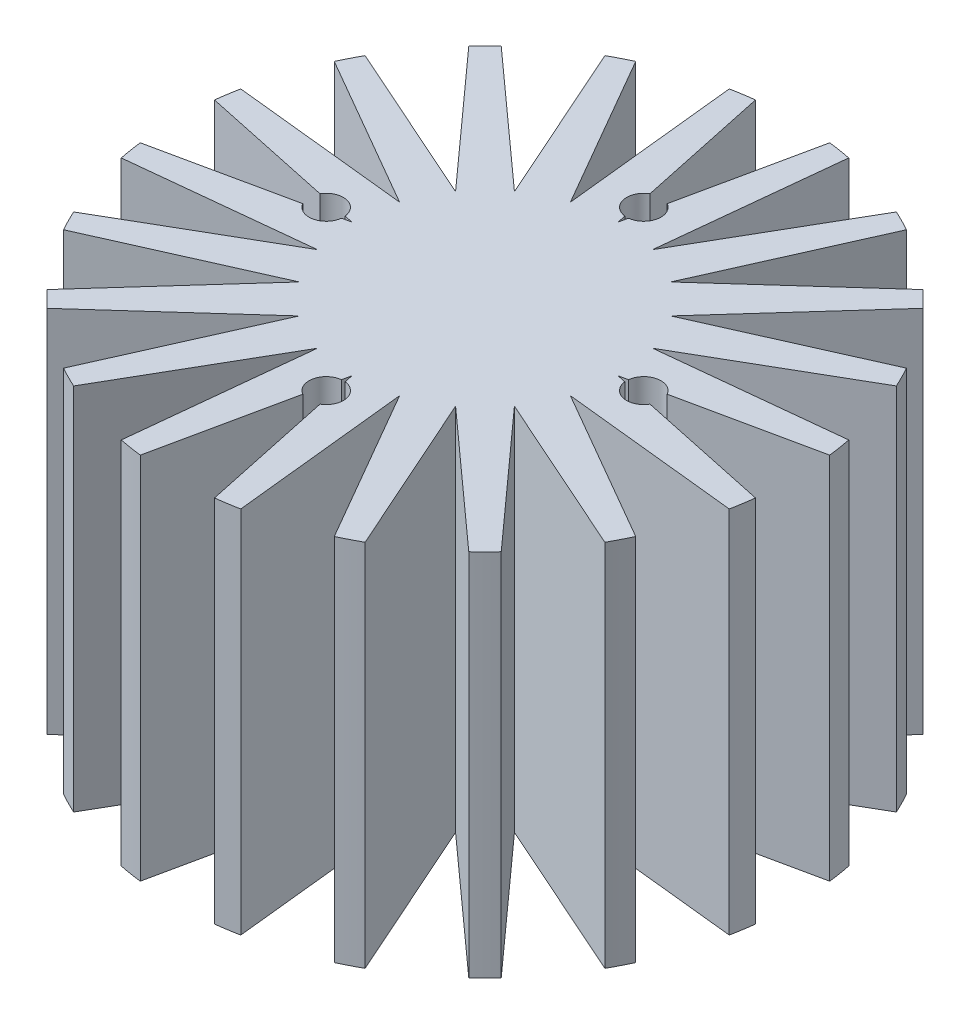
SolidWorks part; units mm, degrees
ref_plane "Front Plane" through (0, 0, 0) normal (0, 0, 1) x (1, 0, 0)
ref_plane "Top Plane" through (0, 0, 0) normal (0, 1, 0) x (1, 0, 0)
ref_plane "Right Plane" through (0, 0, 0) normal (1, 0, 0) x (0, 0, -1)
sketch "Sketch1" plane through (0, 0, 0) normal (0, 1, 0) x (1, 0, 0)
  circle A0 centre (0, 0) radius 18.05
  dimension "D1" = 36.1
extrude "Boss-Extrude1" add sketch "Sketch1" along normal blind 21.5
sketch "Sketch2" plane through (0, 21.5, 0) normal (0, 1, 0) x (1, 0, 0)
  line L0 (0, 0) -> (0, 18.05) construction
  line L1 (0, 0) -> (18.05, 0) construction
  line L2 (0, 0) -> (0, -18.05) construction
  line L3 (0, 0) -> (-18.05, 0) construction
  circle A0 centre (0, 0) radius 9.25 construction
  circle A1 centre (0, 0) radius 18.05 construction
  circle A2 centre (-9.25, 0) radius 1
  circle A3 centre (0, 9.25) radius 1
  circle A4 centre (9.25, 0) radius 1
  circle A5 centre (0, -9.25) radius 1
  dimension "D1" = 18.5
  dimension "D2" = 2
  dimension "D3" = 16.5
extrude "Cut-Extrude1" cut sketch "Sketch2" against normal through all
sketch "Sketch3" plane through (0, 21.5, 0) normal (0, 1, 0) x (1, 0, 0)
  line L0 (0, 0) -> (0, 22.6279) construction
  line L1 (0, 0) -> (4.0093, 22.7377) construction
  line L2 (0, 0) -> (-4.0002, 22.6865) construction
  line L3 (-2.1617, 17.9201) -> (0, 7.75)
  line L4 (0, 7.75) -> (2.1617, 17.9201)
  circle A0 centre (0, 0) radius 7.75
  circle A1 centre (0, 0) radius 18.05 construction
  circle A2 centre (0, 0) radius 18.05
  circle M8 centre (0, 9.25) radius 1
  circle M10 centre (0, 0) radius 18.05
  dimension "D1" = 15.5
  dimension "D2" = 10
  dimension "D3" = 10
  dimension "D4" = 12
  dimension "D5" = 12
extrude "Cut-Extrude2" cut sketch "Sketch3" against normal through all contours L4 L3 M8 M10 | L3 L4 M8 | L4 L3 M8
pattern_circular "CirPattern1" count 20 over 360 about axis through (0, 0, 0) along (0, 1, 0) of "Cut-Extrude2"
